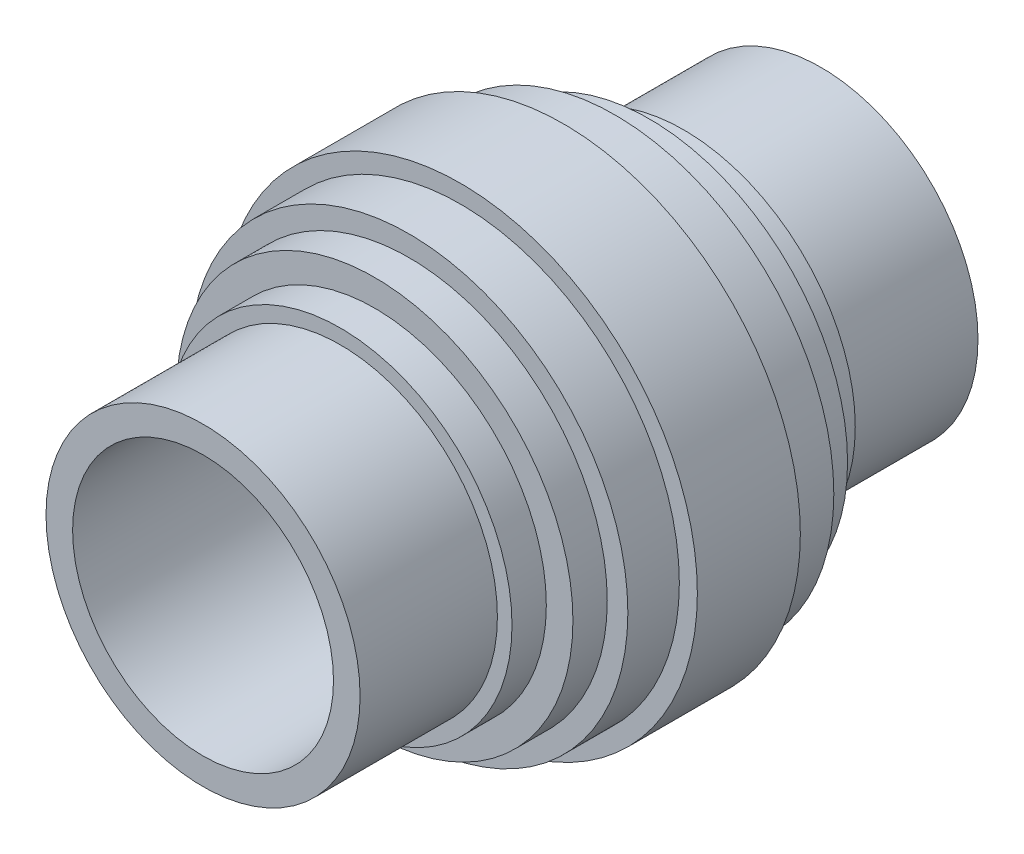
SolidWorks part; units mm, degrees
ref_plane "Front Plane" through (0, 0, 0) normal (0, 0, 1) x (1, 0, 0)
ref_plane "Top Plane" through (0, 0, 0) normal (0, 1, 0) x (1, 0, 0)
ref_plane "Right Plane" through (0, 0, 0) normal (1, 0, 0) x (0, 0, -1)
sketch "S01 - Ball and misalignment spacer land 1" plane through (0, 0, 0) normal (0, 0, 1) x (1, 0, 0)
  circle A0 centre (0, 0) radius 1.83
  circle A1 centre (0, 0) radius 1.52
  dimension "D1" = 3.04
  dimension "D2" = 3.66
extrude "01 - Ball and misalignment spacer land 1" add sketch "S01 - Ball and misalignment spacer land 1" along normal blind 1.6 from offset 3.6
sketch "S02 - Ball and misalignment spacer land 2" plane through (0, 0, 0) normal (0, 0, 1) x (1, 0, 0)
  circle A0 centre (0, 0) radius 2
  circle A1 centre (0, 0) radius 1.52
  dimension "D1" = 3.04
  dimension "D2" = 4
extrude "02 - Ball and misalignment spacer land 2" add sketch "S02 - Ball and misalignment spacer land 2" along normal blind 0.4 from offset 2
sketch "S03 - Ball and misalignment spacer land 3" plane through (0, 0, 0) normal (0, 0, 1) x (1, 0, 0)
  circle A0 centre (0, 0) radius 2.31
  circle A1 centre (0, 0) radius 1.52
  dimension "D1" = 3.04
  dimension "D2" = 4.62
extrude "03 - Ball and misalignment spacer land 3" add sketch "S03 - Ball and misalignment spacer land 3" along normal blind 0.4 from offset 1.6
sketch "S04 - Ball and misalignment spacer land 4" plane through (0, 0, 0) normal (0, 0, 1) x (1, 0, 0)
  circle A0 centre (0, 0) radius 2.55
  circle A1 centre (0, 0) radius 1.52
  dimension "D1" = 3.04
  dimension "D2" = 5.1
extrude "04 - Ball and misalignment spacer land 4" add sketch "S04 - Ball and misalignment spacer land 4" along normal blind 0.6 from offset 1.2
sketch "S05 - Ball and misalignment spacer land 5" plane through (0, 0, 0) normal (0, 0, 1) x (1, 0, 0)
  circle A0 centre (0, 0) radius 2.76
  circle A1 centre (0, 0) radius 1.52
  dimension "D1" = 3.04
  dimension "D2" = 5.52
extrude "05 - Ball and misalignment spacer land 5" add sketch "S05 - Ball and misalignment spacer land 5" along normal blind 1.2 from offset 0.6
sketch "S06 - Ball and misalignment spacer land 6" plane through (0, 0, 0) normal (0, 0, 1) x (1, 0, 0)
  circle A0 centre (0, 0) radius 2.55
  circle A1 centre (0, 0) radius 1.52
  dimension "D1" = 3.04
  dimension "D2" = 5.1
extrude "06 - Ball and misalignment spacer land 6" add sketch "S06 - Ball and misalignment spacer land 6" along normal blind 0.6 from offset 0.6
sketch "S07 - Ball and misalignment spacer land 7" plane through (0, 0, 0) normal (0, 0, 1) x (1, 0, 0)
  circle A0 centre (0, 0) radius 2.31
  circle A1 centre (0, 0) radius 1.52
  dimension "D1" = 3.04
  dimension "D2" = 4.62
extrude "07 - Ball and misalignment spacer land 7" add sketch "S07 - Ball and misalignment spacer land 7" along normal blind 0.4 from offset 1.2
sketch "S08 - Ball and misalignment spacer land 8" plane through (0, 0, 0) normal (0, 0, 1) x (1, 0, 0)
  circle A0 centre (0, 0) radius 2
  circle A1 centre (0, 0) radius 1.52
  dimension "D1" = 3.04
  dimension "D2" = 4
extrude "08 - Ball and misalignment spacer land 8" add sketch "S08 - Ball and misalignment spacer land 8" along normal blind 0.4 from offset 1.6
sketch "S09 - Ball and misalignment spacer land 9" plane through (0, 0, 0) normal (0, 0, 1) x (1, 0, 0)
  circle A0 centre (0, 0) radius 1.83
  circle A1 centre (0, 0) radius 1.52
  dimension "D1" = 3.04
  dimension "D2" = 3.66
extrude "09 - Ball and misalignment spacer land 9" add sketch "S09 - Ball and misalignment spacer land 9" along normal blind 1.6 from offset 2
